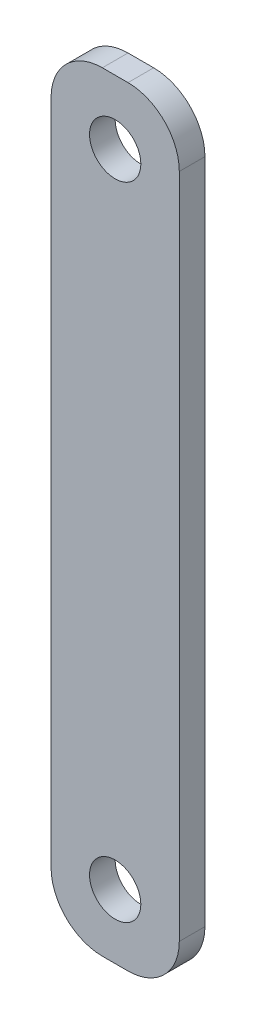
SolidWorks part; units mm, degrees
ref_plane "Front Plane" through (0, 0, 0) normal (0, 0, 1) x (1, 0, 0)
ref_plane "Top Plane" through (0, 0, 0) normal (0, 1, 0) x (1, 0, 0)
ref_plane "Right Plane" through (0, 0, 0) normal (1, 0, 0) x (0, 0, -1)
sketch "Sketch1" plane through (0, 0, 0) normal (0, 0, 1) x (1, 0, 0)
  line L1 (0, 0) -> (5, 0)
  line L2 (0, 0) -> (0, 30)
  line L4 (5, 0) -> (5, 30)
  line L5 (0, 30) -> (5, 30)
  circle A0 centre (2.5, 2.5) radius 1
  circle A1 centre (2.5, 27.5) radius 1
  dimension "D2" = 30
  dimension "D3" = 2
  dimension "D4" = 2
  dimension "D1" = 5
extrude "Boss-Extrude1" add sketch "Sketch1" along normal blind 1
fillet "Fillet5" radius 2 1 edges at (5, 0, 0.5)
fillet "Fillet6" radius 2 1 edges at (0, 0, 0.5)
fillet "Fillet7" radius 2 1 edges at (0, 30, 0.5)
fillet "Fillet8" radius 2 1 edges at (5, 30, 0.5)
